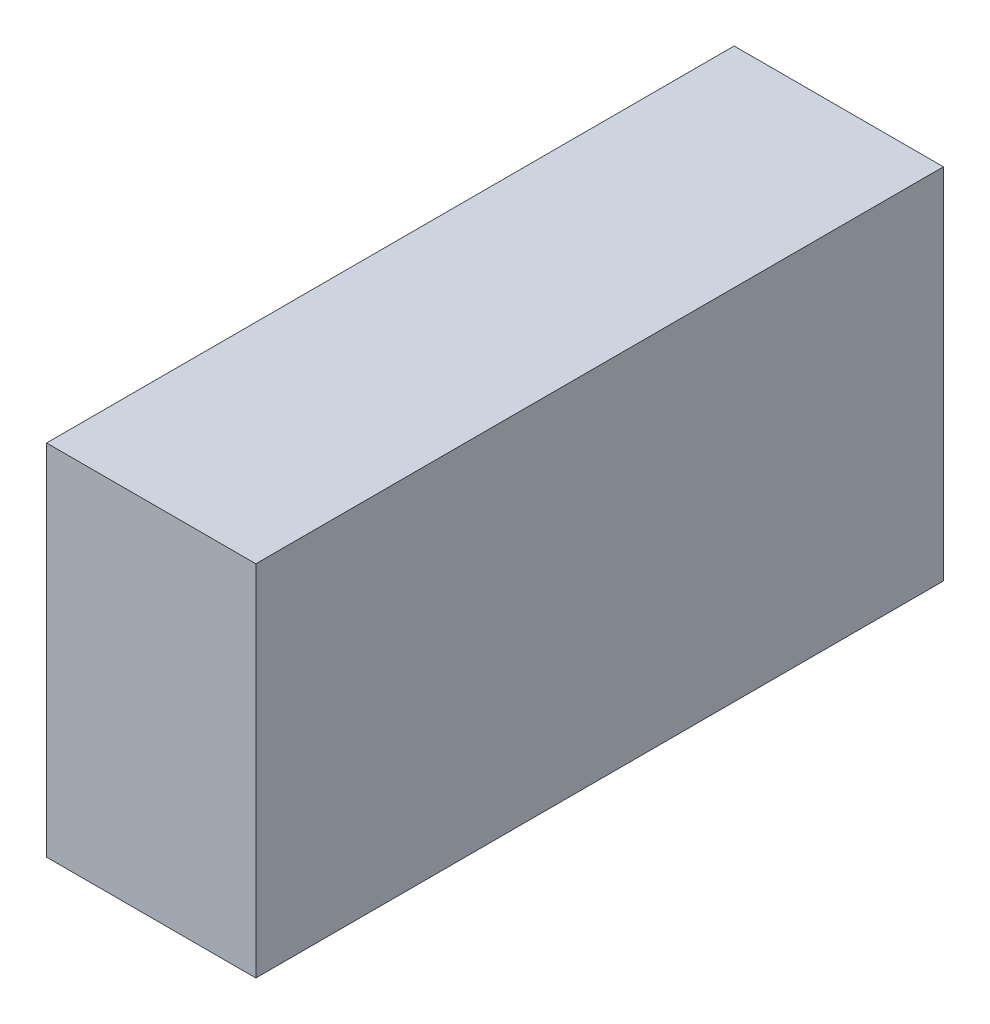
SolidWorks part; units mm, degrees
ref_plane "Front Plane" through (0, 0, 0) normal (0, 0, 1) x (1, 0, 0)
ref_plane "Top Plane" through (0, 0, 0) normal (0, 1, 0) x (1, 0, 0)
ref_plane "Right Plane" through (0, 0, 0) normal (1, 0, 0) x (0, 0, -1)
sketch "Sketch1" plane through (0, 0, 0) normal (0, 0, 1) x (1, 0, 0)
  line L1 (-88.9, 152.4) -> (88.9, 152.4)
  line L2 (-88.9, 152.4) -> (-88.9, -152.4)
  line L3 (-88.9, -152.4) -> (88.9, -152.4)
  line L4 (88.9, 152.4) -> (88.9, -152.4)
  line L5 (-88.9, 152.4) -> (88.9, -152.4) construction
  line L6 (-88.9, -152.4) -> (88.9, 152.4) construction
  point P0 (0, 0)
  dimension "D1" = 304.8
  dimension "D2" = 177.8
extrude "Boss-Extrude1" add sketch "Sketch1" along normal blind 584.2
